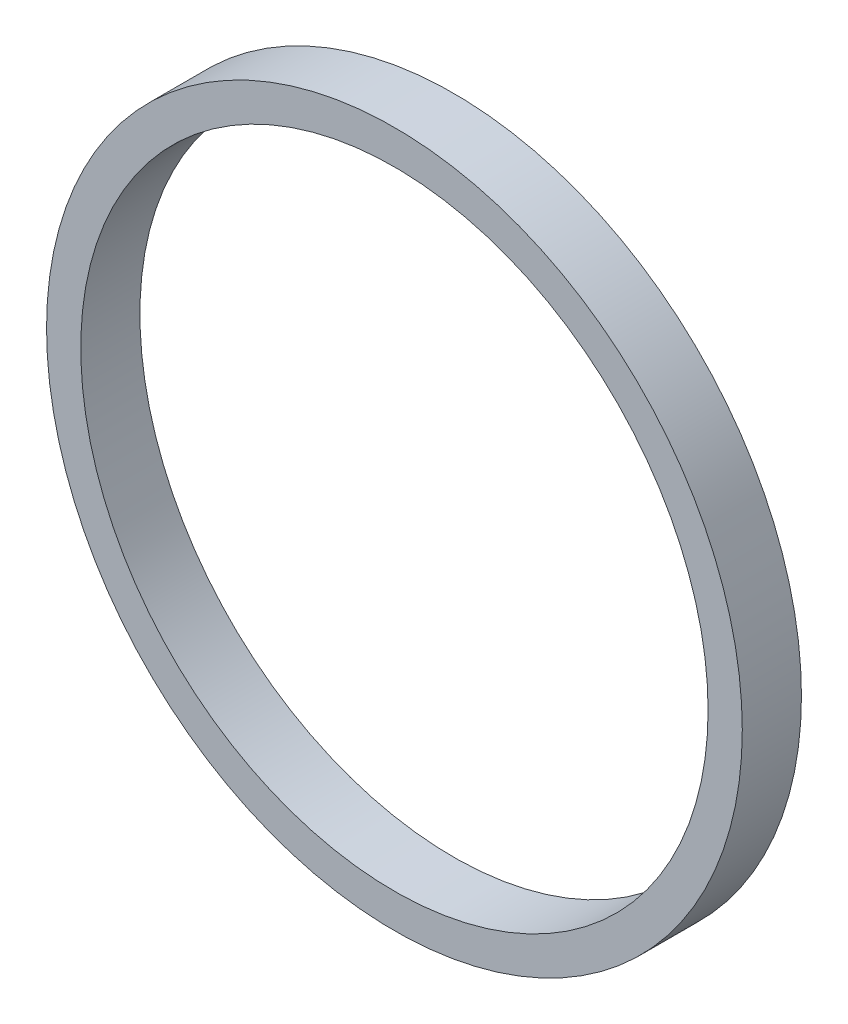
SolidWorks part; units mm, degrees
material "6061-T6 (SS)"
ref_plane "Front Plane" through (0, 0, 0) normal (0, 0, 1) x (1, 0, 0)
ref_plane "Top Plane" through (0, 0, 0) normal (0, 1, 0) x (1, 0, 0)
ref_plane "Right Plane" through (0, 0, 0) normal (1, 0, 0) x (0, 0, -1)
sketch "Sketch1" plane through (0, 0, 0) normal (1, 0, 0) x (0, 0, -1)
  line L0 (-35.627, 0) -> (36.4528, 0) construction
  line L1 (-2.3622, 25.05) -> (2.3622, 25.05)
  line L2 (-2.3622, 25.05) -> (-2.3622, 27.7812)
  line L3 (2.3622, 25.05) -> (2.3622, 27.7812)
  line L4 (-2.3622, 27.7812) -> (2.3622, 27.7812)
  line L5 (0, 0) -> (0, 25.05) construction
  dimension "D1" = 50.1
  dimension "D2" = 55.5625
  dimension "D3" = 4.7244
revolve "Revolve1" add sketch "Sketch1" angle 360 about L0
